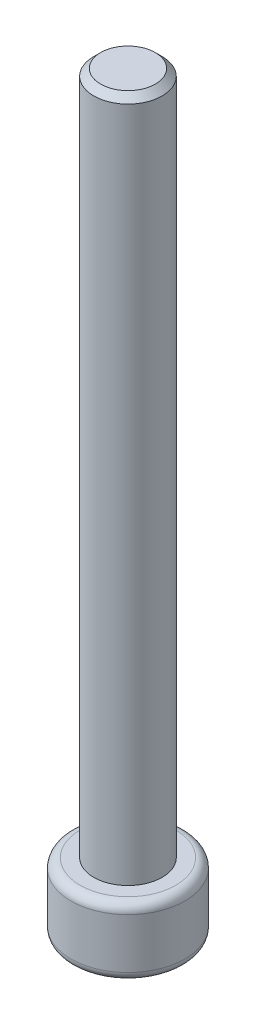
SolidWorks part; units mm, degrees
ref_plane "Front Plane" through (0, 0, 0) normal (0, 0, 1) x (1, 0, 0)
ref_plane "Top Plane" through (0, 0, 0) normal (0, 1, 0) x (1, 0, 0)
ref_plane "Right Plane" through (0, 0, 0) normal (1, 0, 0) x (0, 0, -1)
sketch "Sketch1" plane through (0, 0, 0) normal (0, 1, 0) x (1, 0, 0)
  circle A0 centre (0, 0) radius 2.5
  dimension "D1" = 5
extrude "Boss-Extrude1" add sketch "Sketch1" along normal blind 3
sketch "Sketch2" plane through (0, 3, 0) normal (0, 1, 0) x (1, 0, 0)
  circle A0 centre (0, 0) radius 1.5
  dimension "D1" = 3
extrude "Boss-Extrude2" add sketch "Sketch2" along normal blind 30
chamfer "Chamfer1" distance 0.3 angle 45 1 edges at (0, 33, 1.5)
fillet "Fillet1" radius 0.4 2 edges at (0, 0, 2.5) (0, 3, 2.5)
sketch "Sketch3" plane through (0, 0, 0) normal (0, -1, 0) x (1, 0, 0)
  line L1 (1.4434, 0) -> (0.7217, 1.25)
  line L2 (0.7217, 1.25) -> (-0.7217, 1.25)
  line L3 (-0.7217, 1.25) -> (-1.4434, 0)
  line L4 (-1.4434, 0) -> (-0.7217, -1.25)
  line L5 (-0.7217, -1.25) -> (0.7217, -1.25)
  line L6 (0.7217, -1.25) -> (1.4434, 0)
  circle A0 centre (0, 0) radius 1.25 construction
  dimension "D1" = 2.5
extrude "Cut-Extrude1" cut sketch "Sketch3" against normal blind 1.5
